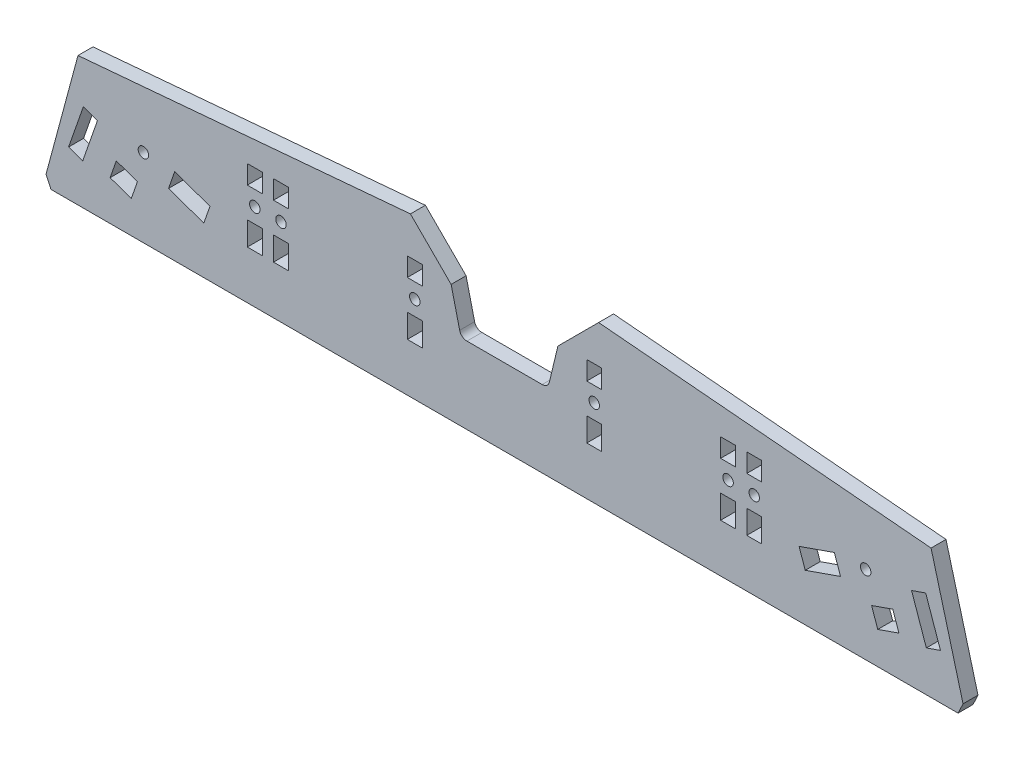
SolidWorks part; units mm, degrees
ref_plane "前视基准面" through (0, 0, 0) normal (0, 0, 1) x (1, 0, 0)
ref_plane "上视基准面" through (0, 0, 0) normal (0, 1, 0) x (1, 0, 0)
ref_plane "右视基准面" through (0, 0, 0) normal (1, 0, 0) x (0, 0, -1)
sketch "草图1" plane through (0, 0, 0) normal (0, 0, 1) x (1, 0, 0)
  line L1 (-110, 17.5) -> (110, 17.5)
  line L2 (-110, 17.5) -> (-110, -17.5)
  line L3 (-110, -17.5) -> (110, -17.5)
  line L4 (110, 17.5) -> (110, -17.5)
  line L5 (-110, 17.5) -> (110, -17.5) construction
  line L6 (-110, -17.5) -> (110, 17.5) construction
  point P0 (0, 0)
  dimension "D1" = 220
  dimension "D2" = 35
extrude "凸台-拉伸1" add sketch "草图1" along normal blind 4
ref_plane "基准面1" through (0, 0, 0) normal (-1, 0, 0) x (0, 0, 1)
sketch "草图2" plane through (0, 0, 4) normal (0, 0, 1) x (1, 0, 0)
  line L0 (0, 17.52) -> (-17, 17.5)
  line L1 (0, 44.8511) -> (0, -44.8511) construction
  line L2 (110, 17.5) -> (-110, 17.5) construction
  line L3 (-17, 17.5) -> (-17, 0)
  line L4 (-17, 0) -> (17, 0)
  line L5 (17, 0) -> (17, 17.5)
  line L6 (17, 17.5) -> (0, 17.52)
extrude "切除-拉伸1" cut sketch "草图2" against normal blind 10
chamfer "倒角1" distance 5 angle 45 2 edges at (-17, 17.5, 2) (17, 17.5, 2)
sketch "草图3" plane through (0, 0, 0) normal (0, 0, -1) x (-1, 0, 0)
  line L0 (-17, 0) -> (-17, 12.5) construction
  line L1 (-17, 0) -> (-17, 12.5)
  line L2 (17, 12.5) -> (17, 0) construction
  line L3 (17, 12.5) -> (17, 0)
  line L4 (-17, 0) -> (-14, 0)
  line L5 (17, 0) -> (-17, 0) construction
  line L6 (-14, 0) -> (-17, 12.5)
  line L7 (17, 0) -> (14, 0)
  line L8 (14, 0) -> (17, 12.5)
extrude "凸台-拉伸2" add sketch "草图3" against normal up to surface (4 mm away) up to face at (0, 6, 4)
sketch "草图4" plane through (0, 0, 0) normal (0, 0, -1) x (-1, 0, 0)
  line L2 (-22, 17.5) -> (-29.0711, 24.5711)
  line L3 (-29.0711, 24.5711) -> (-110, 17.5)
  line L4 (-110, 17.5) -> (-22, 17.5)
  line L6 (22, 17.5) -> (29.0711, 24.5711)
  line L7 (29.0711, 24.5711) -> (110, 17.5)
  line L8 (110, 17.5) -> (22, 17.5)
extrude "凸台-拉伸3" add sketch "草图4" against normal up to surface (4 mm away) up to face at (0, 6, 4)
ref_plane "基准面2" through (0, 0, 0) normal (1, 0, 0) x (0, 0, -1)
sketch "草图7" plane through (0, 0, 0) normal (0, 0, -1) x (-1, 0, 0)
  line L3 (-110, 17.5) -> (-115.9772, 16.9777)
  line L4 (-110, -17.5) -> (-112.5, -17.5)
  line L5 (-112.5, -17.5) -> (-115.9772, 16.9777)
  line L6 (-110, -17.5) -> (-110, 17.5) construction
  line L7 (-110, -17.5) -> (-110, 17.5)
  dimension "D1" = 6
  dimension "D2" = 2.5
extrude "凸台-拉伸4" add sketch "草图7" against normal up to surface (4 mm away) up to face at (0, 7.4142, 4)
sketch "草图19" plane through (0, 0, 0) normal (0, 0, -1) x (-1, 0, 0)
  line L0 (-17, 12.5) -> (-29.0711, 24.5711) construction
  line L1 (-17, 12.5) -> (-29.0711, 24.5711)
  line L2 (-14, 0) -> (-17, 12.5) construction
  line L3 (-14, 0) -> (-17, 12.5)
  line L4 (14, 0) -> (-14, 0) construction
  line L5 (14, 0) -> (-14, 0)
  line L6 (17, 12.5) -> (14, 0) construction
  line L7 (17, 12.5) -> (14, 0)
  line L8 (29.0711, 24.5711) -> (17, 12.5) construction
  line L9 (29.0711, 24.5711) -> (17, 12.5)
  line L10 (25.1693, 24.912) -> (14.2803, 14.023)
  line L11 (14.2803, 14.023) -> (11.6348, 3)
  line L12 (11.6348, 3) -> (-11.6348, 3)
  line L13 (-11.6348, 3) -> (-14.2803, 14.023)
  line L14 (-14.2803, 14.023) -> (-25.6496, 25.3922)
  line L15 (-14.2803, 14.023) -> (-26.9498, 26.6924) construction
  line L17 (-29.0711, 24.5711) -> (-25.6496, 25.3922)
  line L18 (29.0711, 24.5711) -> (25.1693, 24.912)
  line L20 (26.9497, 26.6924) -> (14.2803, 14.023) construction
  dimension "D1" = 3
extrude "凸台-拉伸7" add sketch "草图19" against normal up to surface (4 mm away) up to face at (0.8477, 7.362, 4)
fillet "圆角1" radius 2 2 edges at (-11.6348, 3, 2) (11.6348, 3, 2)
extrude "切除-拉伸8" cut sketch "草图21" against normal blind 4
sketch "草图21" plane through (133.9432, -40.8803, 0) normal (0, 0, -1) x (1, 0, 0)
  line L8 (-69.1432, -55.6471) -> (-65.1432, -55.6471)
  line L9 (-65.1432, -55.6471) -> (-65.1432, -50.6471)
  line L10 (-65.1432, -50.6471) -> (-69.1432, -50.6471)
  line L11 (-69.1432, -50.6471) -> (-69.1432, -55.6471)
  line L16 (-76.1432, -55.6471) -> (-72.1432, -55.6471)
  line L17 (-72.1432, -55.6471) -> (-72.1432, -50.6471)
  line L18 (-72.1432, -50.6471) -> (-76.1432, -50.6471)
  line L19 (-76.1432, -50.6471) -> (-76.1432, -55.6471)
  line L24 (-65.1432, -36.2992) -> (-69.1432, -36.2992)
  line L25 (-69.1432, -36.2992) -> (-69.1432, -42.5982)
  line L26 (-69.1432, -42.5982) -> (-65.1432, -42.5982)
  line L27 (-65.1432, -42.5982) -> (-65.1432, -36.2992)
  line L32 (-72.1432, -36.2992) -> (-76.1432, -36.2992)
  line L33 (-76.1432, -36.2992) -> (-76.1432, -42.5982)
  line L34 (-76.1432, -42.5982) -> (-72.1432, -42.5982)
  line L35 (-72.1432, -42.5982) -> (-72.1432, -36.2992)
  line L40 (-111.9432, -55.6471) -> (-107.9432, -55.6471)
  line L41 (-107.9432, -55.6471) -> (-107.9432, -50.6471)
  line L42 (-107.9432, -50.6471) -> (-111.9432, -50.6471)
  line L43 (-111.9432, -50.6471) -> (-111.9432, -55.6471)
  line L48 (-107.9432, -36.2992) -> (-111.9432, -36.2992)
  line L49 (-111.9432, -36.2992) -> (-111.9432, -42.5982)
  line L50 (-111.9432, -42.5982) -> (-107.9432, -42.5982)
  line L51 (-107.9432, -42.5982) -> (-107.9432, -36.2992)
  line L56 (-155.9432, -36.2992) -> (-159.9432, -36.2992)
  line L57 (-159.9432, -36.2992) -> (-159.9432, -42.5982)
  line L58 (-159.9432, -42.5982) -> (-155.9432, -42.5982)
  line L59 (-155.9432, -42.5982) -> (-155.9432, -36.2992)
  line L64 (-159.9432, -55.6471) -> (-155.9432, -55.6471)
  line L65 (-155.9432, -55.6471) -> (-155.9432, -50.6471)
  line L66 (-155.9432, -50.6471) -> (-159.9432, -50.6471)
  line L67 (-159.9432, -50.6471) -> (-159.9432, -55.6471)
  line L72 (-198.7432, -36.2992) -> (-202.7432, -36.2992)
  line L73 (-202.7432, -36.2992) -> (-202.7432, -42.5982)
  line L74 (-202.7432, -42.5982) -> (-198.7432, -42.5982)
  line L75 (-198.7432, -42.5982) -> (-198.7432, -36.2992)
  line L80 (-191.7432, -36.2992) -> (-195.7432, -36.2992)
  line L81 (-195.7432, -36.2992) -> (-195.7432, -42.5982)
  line L82 (-195.7432, -42.5982) -> (-191.7432, -42.5982)
  line L83 (-191.7432, -42.5982) -> (-191.7432, -36.2992)
  line L88 (-195.7432, -55.6471) -> (-191.7432, -55.6471)
  line L89 (-191.7432, -55.6471) -> (-191.7432, -50.6471)
  line L90 (-191.7432, -50.6471) -> (-195.7432, -50.6471)
  line L91 (-195.7432, -50.6471) -> (-195.7432, -55.6471)
  line L96 (-202.7432, -55.6471) -> (-198.7432, -55.6471)
  line L97 (-198.7432, -55.6471) -> (-198.7432, -50.6471)
  line L98 (-198.7432, -50.6471) -> (-202.7432, -50.6471)
  line L99 (-202.7432, -50.6471) -> (-202.7432, -55.6471)
extrude "切除-拉伸9" cut sketch "草图22" against normal blind 4
sketch "草图22" plane through (133.9432, -40.8803, 0) normal (0, 0, -1) x (1, 0, 0)
  circle A0 centre (-109.9432, -46.6203) radius 1.4024
  circle A1 centre (-74.1432, -46.6203) radius 1.4024
  circle A2 centre (-67.1432, -46.6203) radius 1.4024
mirror "镜向10" about plane through (0, 0, 0) normal (1, 0, 0) of "切除-拉伸9"
mirror "镜向11" about plane through (0, 0, 0) normal (1, 0, 0) of "凸台-拉伸4"
sketch "草图23" plane through (0, 0, 0) normal (0, 0, -1) x (-1, 0, 0)
  line L0 (115.9772, 16.9777) -> (112.5, -17.5) construction
  line L1 (115.9772, 16.9777) -> (112.5, -17.5)
  line L2 (112.5, -17.5) -> (123.6773, -17.5)
  line L3 (123.6773, -17.5) -> (127.042, 15.8618)
  line L4 (127.042, 15.8618) -> (115.9772, 16.9777)
extrude "凸台-拉伸8" add sketch "草图23" against normal up to surface (4 mm away) up to face at (-22.5976, 5.74, 4)
sketch "草图27" plane through (0, 0, 0) normal (0, 0, -1) x (-1, 0, 0)
  line L0 (123.6773, -17.5) -> (127.042, 15.8618) construction
  line L1 (123.6773, -17.5) -> (127.042, 15.8618)
  line L3 (110, 17.5) -> (115.9772, 16.9777) construction
  line L4 (111.1163, 17.4025) -> (123.6773, -17.5)
  line L5 (111.1163, 17.4025) -> (110.4532, 19.245)
  line L6 (110.4532, 19.245) -> (127.042, 15.8618)
extrude "切除-拉伸14" cut sketch "草图27" against normal blind 10
extrude "切除-拉伸15" cut sketch "草图28" against normal blind 4
sketch "草图28" plane through (133.9432, -40.8803, 0) normal (0, 0, -1) x (1, 0, 0)
  line L8 (-214.3848, -36.0294) -> (-223.8262, -39.3248)
  line L9 (-223.8262, -39.3248) -> (-222.1785, -44.0455)
  line L10 (-222.1785, -44.0455) -> (-212.7371, -40.7501)
  line L11 (-212.7371, -40.7501) -> (-214.3848, -36.0294)
  line L16 (-239.4506, -34.0095) -> (-237.8029, -38.7302)
  line L17 (-237.8029, -38.7302) -> (-232.1381, -36.7529)
  line L18 (-232.1381, -36.7529) -> (-233.7858, -32.0322)
  line L19 (-233.7858, -32.0322) -> (-239.4506, -34.0095)
  line L24 (-242.8305, -45.5676) -> (-246.785, -34.2379)
  line L25 (-246.785, -34.2379) -> (-250.5616, -35.5561)
  line L26 (-250.5616, -35.5561) -> (-246.6071, -46.8858)
  line L27 (-246.6071, -46.8858) -> (-242.8305, -45.5676)
chamfer "倒角2" distance 3 angle 45 1 edges at (-123.6773, -17.5, 2)
extrude "切除-拉伸16" cut sketch "草图29" against normal blind 4
sketch "草图29" plane through (133.9432, -40.8803, 0) normal (0, 0, -1) x (1, 0, 0)
  line L8 (-40.9432, -37.0816) -> (-40.9432, -42.0816)
  line L9 (-40.9432, -42.0816) -> (-34.9432, -42.0816)
  line L10 (-34.9432, -42.0816) -> (-34.9432, -37.0816)
  line L11 (-34.9432, -37.0816) -> (-40.9432, -37.0816)
  line L16 (-57.9432, -52.2489) -> (-47.9432, -52.2489)
  line L17 (-47.9432, -52.2489) -> (-47.9432, -47.2489)
  line L18 (-47.9432, -47.2489) -> (-57.9432, -47.2489)
  line L19 (-57.9432, -47.2489) -> (-57.9432, -52.2489)
  line L24 (-23.9432, -46.8803) -> (-23.9432, -34.8803)
  line L25 (-23.9432, -34.8803) -> (-27.9432, -34.8803)
  line L26 (-27.9432, -34.8803) -> (-27.9432, -46.8803)
  line L27 (-27.9432, -46.8803) -> (-23.9432, -46.8803)
extrude "切除-拉伸17" cut sketch "草图30" against normal blind 4
sketch "草图30" plane through (133.9432, -40.8803, 0) normal (0, 0, -1) x (1, 0, 0)
  circle A0 centre (-39.9432, -49.7489) radius 1.4
  circle A1 centre (-230.5555, -44.3215) radius 1.4
sketch "草图31" plane through (0, 0, 0) normal (0, 0, -1) x (-1, 0, 0)
  line L2 (111.1163, 17.4025) -> (114.1049, 17.1413)
  line L3 (114.1049, 17.1413) -> (122.6614, -14.6772)
  line L4 (122.6614, -14.6772) -> (111.1163, 17.4025)
extrude "凸台-拉伸9" add sketch "草图31" against normal up to surface (4 mm away) up to face at (92.6, 8.8686, 4)
sketch "草图35" plane through (0, 0, 0) normal (1, 0, 0) x (0, 0, -1)
  circle A0 centre (0, 0) radius 44.6442
extrude "切除-拉伸19" cut sketch "草图35" along normal through all
sketch "草图36" plane through (0, 0, 0) normal (0, 0, -1) x (-1, 0, 0)
  line L0 (22, 9.7668) -> (26, 9.7668) construction
  line L1 (22, 9.7668) -> (26, 9.7668)
  line L2 (22, 14.7668) -> (22, 9.7668) construction
  line L3 (22, 14.7668) -> (22, 9.7668)
  line L4 (26, 14.7668) -> (22, 14.7668) construction
  line L5 (26, 14.7668) -> (22, 14.7668)
  line L6 (26, 9.7668) -> (26, 14.7668) construction
  line L7 (26, 9.7668) -> (26, 14.7668)
  line L8 (26, 1.7179) -> (22, 1.7179) construction
  line L9 (0, 3) -> (0, -17.5)
  line L10 (0, -17.5) -> (121.3327, -17.5)
  line L11 (121.3327, -17.5) -> (122.6614, -14.6772)
  line L12 (122.6614, -14.6772) -> (114.1049, 17.1413)
  line L13 (114.1049, 17.1413) -> (110, 17.5)
  line L14 (110, 17.5) -> (25.1693, 24.912)
  line L15 (25.1693, 24.912) -> (14.2803, 14.023)
  line L16 (14.2803, 14.023) -> (12.0028, 4.5333)
  line L17 (10.058, 3) -> (0, 3)
  line L19 (-121.3327, -17.5) -> (121.3327, -17.5)
  line L20 (121.3327, -17.5) -> (122.6614, -14.6772)
  line L21 (122.6614, -14.6772) -> (114.1049, 17.1413)
  line L22 (114.1049, 17.1413) -> (110, 17.5)
  line L23 (110, 17.5) -> (25.1693, 24.912)
  line L24 (25.1693, 24.912) -> (14.2803, 14.023)
  line L25 (14.2803, 14.023) -> (12.0028, 4.5333)
  line L26 (10.058, 3) -> (-10.058, 3)
  line L27 (26, 1.7179) -> (22, 1.7179)
  line L28 (22, 1.7179) -> (22, -4.5811) construction
  line L29 (22, 1.7179) -> (22, -4.5811)
  line L30 (22, -4.5811) -> (26, -4.5811) construction
  line L31 (22, -4.5811) -> (26, -4.5811)
  line L32 (26, -4.5811) -> (26, 1.7179) construction
  line L33 (26, -4.5811) -> (26, 1.7179)
  line L34 (80.4417, -4.8509) -> (89.8831, -1.5555) construction
  line L35 (80.4417, -4.8509) -> (89.8831, -1.5555)
  line L36 (88.2354, 3.1652) -> (78.794, -0.1302) construction
  line L37 (88.2354, 3.1652) -> (78.794, -0.1302)
  line L38 (78.794, -0.1302) -> (80.4417, -4.8509) construction
  line L39 (78.794, -0.1302) -> (80.4417, -4.8509)
  line L40 (89.8831, -1.5555) -> (88.2354, 3.1652) construction
  line L41 (89.8831, -1.5555) -> (88.2354, 3.1652)
  line L42 (57.8, 1.7179) -> (57.8, -4.5811) construction
  line L43 (57.8, 1.7179) -> (57.8, -4.5811)
  line L44 (61.8, 1.7179) -> (57.8, 1.7179) construction
  line L45 (61.8, 1.7179) -> (57.8, 1.7179)
  line L46 (57.8, -4.5811) -> (61.8, -4.5811) construction
  line L47 (57.8, -4.5811) -> (61.8, -4.5811)
  line L48 (61.8, -4.5811) -> (61.8, 1.7179) construction
  line L49 (61.8, -4.5811) -> (61.8, 1.7179)
  line L50 (57.8, 9.7668) -> (61.8, 9.7668) construction
  line L51 (57.8, 9.7668) -> (61.8, 9.7668)
  line L52 (57.8, 14.7668) -> (57.8, 9.7668) construction
  line L53 (57.8, 14.7668) -> (57.8, 9.7668)
  line L54 (61.8, 14.7668) -> (57.8, 14.7668) construction
  line L55 (61.8, 14.7668) -> (57.8, 14.7668)
  line L56 (61.8, 9.7668) -> (61.8, 14.7668) construction
  line L57 (61.8, 9.7668) -> (61.8, 14.7668)
  line L58 (68.8, 14.7668) -> (64.8, 14.7668) construction
  line L59 (68.8, 14.7668) -> (64.8, 14.7668)
  line L60 (64.8, 14.7668) -> (64.8, 9.7668) construction
  line L61 (64.8, 14.7668) -> (64.8, 9.7668)
  line L62 (112.8419, -6.6424) -> (116.6184, -5.3242) construction
  line L63 (116.6184, -5.3242) -> (112.6639, 6.0055) construction
  line L64 (112.6639, 6.0055) -> (108.8874, 4.6873) construction
  line L65 (108.8874, 4.6873) -> (112.8419, -6.6424) construction
  line L66 (105.5075, -6.8708) -> (103.8598, -2.1501) construction
  line L67 (99.8426, -8.8481) -> (105.5075, -6.8708) construction
  line L68 (103.8598, -2.1501) -> (98.1949, -4.1274) construction
  line L69 (98.1949, -4.1274) -> (99.8426, -8.8481) construction
  line L70 (68.8, -4.5811) -> (68.8, 1.7179) construction
  line L71 (64.8, -4.5811) -> (68.8, -4.5811) construction
  line L72 (64.8, 1.7179) -> (64.8, -4.5811) construction
  line L73 (68.8, 1.7179) -> (64.8, 1.7179) construction
  line L74 (68.8, 9.7668) -> (68.8, 14.7668) construction
  line L75 (64.8, 9.7668) -> (68.8, 9.7668) construction
  line L76 (112.8419, -6.6424) -> (116.6184, -5.3242)
  line L77 (116.6184, -5.3242) -> (112.6639, 6.0055)
  line L78 (112.6639, 6.0055) -> (108.8874, 4.6873)
  line L79 (108.8874, 4.6873) -> (112.8419, -6.6424)
  line L80 (105.5075, -6.8708) -> (103.8598, -2.1501)
  line L81 (99.8426, -8.8481) -> (105.5075, -6.8708)
  line L82 (103.8598, -2.1501) -> (98.1949, -4.1274)
  line L83 (98.1949, -4.1274) -> (99.8426, -8.8481)
  line L84 (68.8, -4.5811) -> (68.8, 1.7179)
  line L85 (64.8, -4.5811) -> (68.8, -4.5811)
  line L86 (64.8, 1.7179) -> (64.8, -4.5811)
  line L87 (68.8, 1.7179) -> (64.8, 1.7179)
  line L88 (68.8, 9.7668) -> (68.8, 14.7668)
  line L89 (64.8, 9.7668) -> (68.8, 9.7668)
  line L90 (-64.8, 9.7668) -> (-68.8, 9.7668)
  line L91 (-68.8, 9.7668) -> (-68.8, 14.7668)
  line L92 (-68.8, 1.7179) -> (-64.8, 1.7179)
  line L93 (-64.8, 1.7179) -> (-64.8, -4.5811)
  line L94 (-64.8, -4.5811) -> (-68.8, -4.5811)
  line L95 (-68.8, -4.5811) -> (-68.8, 1.7179)
  line L96 (-98.1949, -4.1274) -> (-99.8426, -8.8481)
  line L97 (-103.8598, -2.1501) -> (-98.1949, -4.1274)
  line L98 (-99.8426, -8.8481) -> (-105.5075, -6.8708)
  line L99 (-105.5075, -6.8708) -> (-103.8598, -2.1501)
  line L100 (-108.8874, 4.6873) -> (-112.8419, -6.6424)
  line L101 (-112.6639, 6.0055) -> (-108.8874, 4.6873)
  line L102 (-116.6184, -5.3242) -> (-112.6639, 6.0055)
  line L103 (-112.8419, -6.6424) -> (-116.6184, -5.3242)
  line L104 (-64.8, 14.7668) -> (-64.8, 9.7668)
  line L105 (-68.8, 14.7668) -> (-64.8, 14.7668)
  line L106 (-61.8, 9.7668) -> (-61.8, 14.7668)
  line L107 (-61.8, 14.7668) -> (-57.8, 14.7668)
  line L108 (-57.8, 14.7668) -> (-57.8, 9.7668)
  line L109 (-57.8, 9.7668) -> (-61.8, 9.7668)
  line L110 (-61.8, -4.5811) -> (-61.8, 1.7179)
  line L111 (-57.8, -4.5811) -> (-61.8, -4.5811)
  line L112 (-61.8, 1.7179) -> (-57.8, 1.7179)
  line L113 (-57.8, 1.7179) -> (-57.8, -4.5811)
  line L114 (-89.8831, -1.5555) -> (-88.2354, 3.1652)
  line L115 (-78.794, -0.1302) -> (-80.4417, -4.8509)
  line L116 (-88.2354, 3.1652) -> (-78.794, -0.1302)
  line L117 (-80.4417, -4.8509) -> (-89.8831, -1.5555)
  line L118 (-26, -4.5811) -> (-26, 1.7179)
  line L119 (-22, -4.5811) -> (-26, -4.5811)
  line L120 (-22, 1.7179) -> (-22, -4.5811)
  line L121 (-26, 1.7179) -> (-22, 1.7179)
  line L122 (-14.2803, 14.023) -> (-12.0028, 4.5333)
  line L123 (-25.1693, 24.912) -> (-14.2803, 14.023)
  line L124 (-110, 17.5) -> (-25.1693, 24.912)
  line L125 (-114.1049, 17.1413) -> (-110, 17.5)
  line L126 (-122.6614, -14.6772) -> (-114.1049, 17.1413)
  line L127 (-121.3327, -17.5) -> (-122.6614, -14.6772)
  line L128 (-26, 9.7668) -> (-26, 14.7668)
  line L129 (-26, 14.7668) -> (-22, 14.7668)
  line L130 (-22, 14.7668) -> (-22, 9.7668)
  line L131 (-22, 9.7668) -> (-26, 9.7668)
  circle A0 centre (24, 5.74) radius 1.4024 construction
  arc A1 (10.058, 3) -> (12.0028, 4.5333) centre (10.058, 5) ccw
  arc A2 (10.058, 3) -> (12.0028, 4.5333) centre (10.058, 5) ccw
  circle A3 centre (24, 5.74) radius 1.4024
  circle A4 centre (59.8, 5.74) radius 1.4024 construction
  circle A5 centre (59.8, 5.74) radius 1.4024
  circle A6 centre (66.8, 5.74) radius 1.4024 construction
  circle A7 centre (66.8, 5.74) radius 1.4024
  circle A8 centre (96.6123, 3.4412) radius 1.4 construction
  circle A9 centre (96.6123, 3.4412) radius 1.4
  circle A10 centre (-96.6123, 3.4412) radius 1.4
  circle A11 centre (-66.8, 5.74) radius 1.4024
  circle A12 centre (-59.8, 5.74) radius 1.4024
  circle A13 centre (-24, 5.74) radius 1.4024
  arc A14 (-10.058, 3) -> (-12.0028, 4.5333) centre (-10.058, 5) cw
  dimension "D1" = 0
extrude "凸台-拉伸11" add sketch "草图36" against normal up to surface (4 mm away) up to face at (-66.8, 12.2668, 4)
